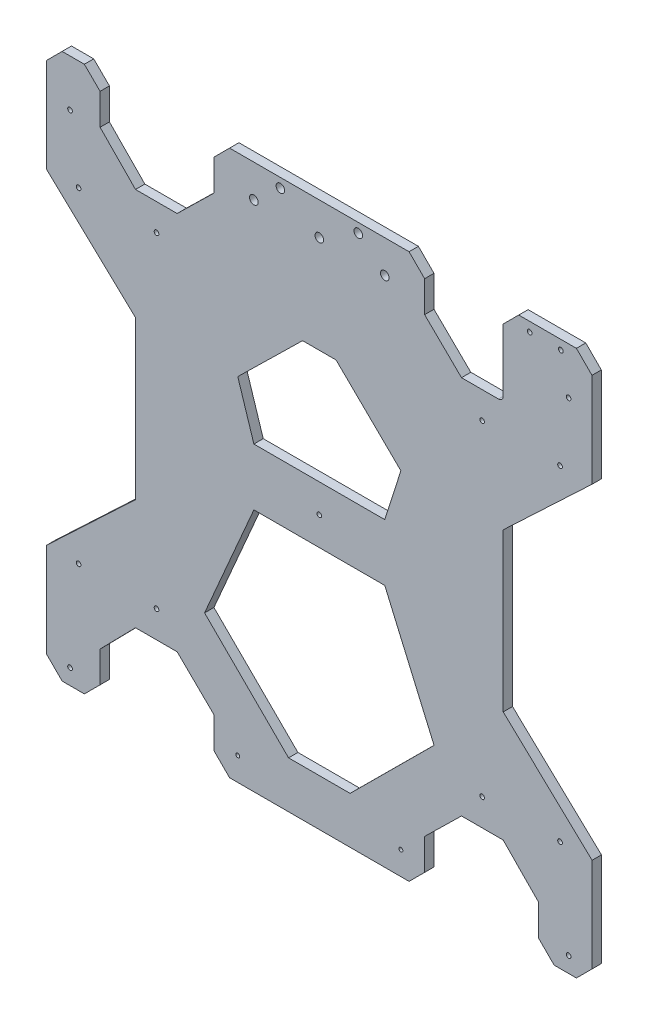
SolidWorks part; units mm, degrees
material "6063-T5"
ref_plane "Piano frontale" through (0, 0, 0) normal (0, 0, 1) x (1, 0, 0)
ref_plane "Piano superiore" through (0, 0, 0) normal (0, 1, 0) x (1, 0, 0)
ref_plane "Piano destro" through (0, 0, 0) normal (1, 0, 0) x (0, 0, -1)
sketch "Schizzo13" plane through (0, 0, 0) normal (0, 0, 1) x (1, 0, 0)
  line L0 (175, 350) -> (175, 0) construction
  line L1 (9.9192, 0) -> (24.2012, 0)
  line L2 (-0.0808, 279.5) -> (57, 225.6111)
  line L3 (217, 193.2869) -> (227.343, 225.6111)
  line L4 (133, 193.2869) -> (217, 193.2869)
  line L5 (350, 175) -> (0, 175) construction
  line L6 (-60.1887, 10) -> (461.2643, 10) construction
  line L7 (279.5, 279.5) -> (279.5, 175) construction
  line L8 (-12.961, 344) -> (386.8832, 344) construction
  line L9 (-12.961, 329) -> (386.8832, 329) construction
  line L10 (185.7509, 30) -> (185.7509, 0) construction
  line L11 (279.5, 70.5) -> (175, 70.5) construction
  line L12 (70.5, 70.5) -> (175, 70.5) construction
  line L13 (185.7509, 15) -> (120.1229, 15) construction
  line L15 (70.5, 279.5) -> (169.5845, 279.5) construction
  line L16 (175, 279.5) -> (329.5, 279.5) construction
  line L17 (329.5, 70.5) -> (329.5, 279.5) construction
  line L18 (20.5, 70.5) -> (329.5, 70.5) construction
  line L19 (20.5, 70.5) -> (20.5, 279.5) construction
  line L20 (175, 279.5) -> (20.5, 279.5) construction
  line L21 (15, -40.9714) -> (15, 408.5301) construction
  line L22 (335, -40.9714) -> (335, 408.5301) construction
  line L23 (-12.961, 320) -> (386.8832, 320) construction
  line L24 (9.9192, 0) -> (-0.0808, 10)
  line L25 (340, 0) -> (350, 10)
  line L26 (107.4046, 340) -> (107.4046, 320)
  line L27 (107.4046, 320) -> (83.7454, 296.8073)
  line L28 (70.5, 279.5) -> (20.5, 279.5) construction
  line L29 (57.0174, 296.8073) -> (34.282, 320)
  line L30 (83.7454, 296.8073) -> (57.0174, 296.8073)
  line L31 (34.282, 320) -> (34.282, 340)
  line L32 (24.2012, 350) -> (9.9192, 350)
  line L33 (133, 193.2869) -> (122.657, 225.6111)
  line L35 (164.2491, 266.3832) -> (185.7509, 266.3832)
  line L36 (122.657, 225.6111) -> (164.2491, 266.3832)
  line L37 (57, 225.6111) -> (57, 175)
  line L38 (227.343, 225.6111) -> (185.7509, 266.3832)
  line L39 (293, 225.6111) -> (293, 124.3889)
  line L40 (350.0808, 279.5) -> (293, 225.6111)
  line L44 (292.9826, 299.8073) -> (292.9826, 340)
  line L46 (117.4046, 0) -> (232.5954, 0)
  line L47 (266.2546, 296.8073) -> (289.9826, 296.8073)
  line L48 (242.5954, 320) -> (266.2546, 296.8073)
  line L49 (242.5954, 340) -> (242.5954, 320)
  line L50 (350.0808, 70.5) -> (293, 124.3889)
  line L53 (350, 10) -> (350.0808, 70.5)
  line L55 (315.718, 30) -> (315.718, 10)
  line L56 (292.9826, 53.1927) -> (315.718, 30)
  line L57 (266.2546, 53.1927) -> (292.9826, 53.1927)
  line L58 (242.5954, 30) -> (266.2546, 53.1927)
  line L59 (242.5954, 10) -> (242.5954, 30)
  line L60 (107.4046, 10) -> (107.4046, 30)
  line L61 (107.4046, 30) -> (83.7454, 53.1927)
  line L62 (83.7454, 53.1927) -> (57.0174, 53.1927)
  line L63 (57.0174, 53.1927) -> (34.282, 30)
  line L64 (34.282, 30) -> (34.2012, 10)
  line L66 (-0.0808, 10) -> (-0.0808, 70.5)
  line L69 (-0.0808, 70.5) -> (57, 124.3889)
  line L70 (57, 124.3889) -> (57, 175)
  line L71 (-0.0808, 279.5) -> (-0.0808, 340)
  line L72 (117.4046, 350) -> (232.5954, 350)
  line L73 (302.9826, 350) -> (340, 350)
  line L74 (350.0808, 279.5) -> (350, 340)
  line L75 (325.718, 0) -> (340, 0)
  line L76 (24.2012, 0) -> (34.2012, 10)
  line L77 (117.4046, 0) -> (107.4046, 10)
  line L78 (232.5954, 0) -> (242.5954, 10)
  line L79 (315.718, 10) -> (325.718, 0)
  line L80 (9.9192, 350) -> (-0.0808, 340)
  line L81 (24.2012, 350) -> (34.282, 340)
  line L82 (107.4046, 340) -> (117.4046, 350)
  line L83 (232.5954, 350) -> (242.5954, 340)
  line L84 (292.9826, 340) -> (302.9826, 350)
  line L85 (340, 350) -> (350, 340)
  line L86 (133, 156.7131) -> (101.3482, 83.6168)
  line L87 (101.3482, 83.6168) -> (155.2542, 30)
  line L88 (155.2542, 30) -> (194.7458, 30)
  line L89 (133, 156.7131) -> (217, 156.7131)
  line L90 (248.6518, 83.6168) -> (194.7458, 30)
  line L91 (217, 156.7131) -> (248.6518, 83.6168)
  circle A0 centre (15, 320) radius 1.5
  circle A1 centre (20.5, 279.5) radius 1.5
  circle A2 centre (70.5, 279.5) radius 1.5
  circle A3 centre (175, 175) radius 1.5
  arc A4 (289.9826, 296.8073) -> (292.9826, 299.8073) centre (289.9826, 299.8073) ccw
  circle A5 centre (20.5, 70.5) radius 1.5
  circle A6 centre (200, 344) radius 2.75
  circle A7 centre (150, 344) radius 2.75
  circle A8 centre (175, 329) radius 2.75
  circle A9 centre (217, 329) radius 2.75
  circle A10 centre (133, 329) radius 2.75
  circle A11 centre (70.5, 70.5) radius 1.5
  circle A12 centre (279.5, 70.5) radius 1.5
  circle A13 centre (329.5, 70.5) radius 1.5
  circle A14 centre (335, 10) radius 1.5
  circle A15 centre (15, 10) radius 1.5
  circle A16 centre (279.5, 279.5) radius 1.5
  circle A17 centre (329.5, 279.5) radius 1.5
  circle A18 centre (335, 320) radius 1.5
  circle A19 centre (310, 344) radius 1.5
  circle A20 centre (330, 344) radius 1.5
  circle A21 centre (122.657, 15) radius 1.25
  circle A22 centre (227.343, 15) radius 1.25
  point P7 (175, 175)
  point P25 (175, 344)
  point P30 (175, 329)
  point P41 (175, 175)
  point P43 (329.5, 175)
  point P46 (15, 320)
  point P54 (335, 320)
  point P55 (335, 10)
  point P56 (15, 10)
  point P57 (15, 320)
  point P58 (335, 320)
  point P59 (15, 10)
  point P60 (335, 10)
  point P93 (292.9826, 296.8073)
  point P155 (175, 156.7131)
  point P156 (175, 30)
  dimension "D5" = 42
  dimension "D6" = 5.5
  dimension "D7" = 25
  dimension "D8" = 15
  dimension "D10" = 154.5
  dimension "D3" = 104.5
  dimension "D17" = 20
  dimension "D2" = 3
  dimension "D14" = 2.5
  dimension "D4" = 104.5
  dimension "D9" = 175
  dimension "D11" = 104.5
  dimension "D12" = 279.5
  dimension "D13" = 104.5
  dimension "D15" = 310
  dimension "D16" = 320
extrude "Estrusione-Estrusione2" add sketch "Schizzo13" against normal blind 6
sketch "Schizzo14" plane through (0, 0, 0) normal (0, 0, 1) x (1, 0, 0)
  line L0 (350, 350) -> (0, 350)
  line L1 (232.5954, 350) -> (117.4046, 350) construction
  line L2 (0, 350) -> (0, 0)
  line L3 (0, 0) -> (350, 0)
  line L4 (117.4046, 0) -> (232.5954, 0) construction
  line L5 (175, 350) -> (175, 0) construction
  line L6 (350, 350) -> (350, 0)
  circle A0 centre (175, 223.4858) radius 4.4409
  circle A1 centre (175, 78.9698) radius 4.6362
sketch "Schizzo15" plane through (0, 0, 0) normal (0, 0, 1) x (1, 0, 0)
  text T0 "HackerBot" font "Lobster 1.4" height 14
